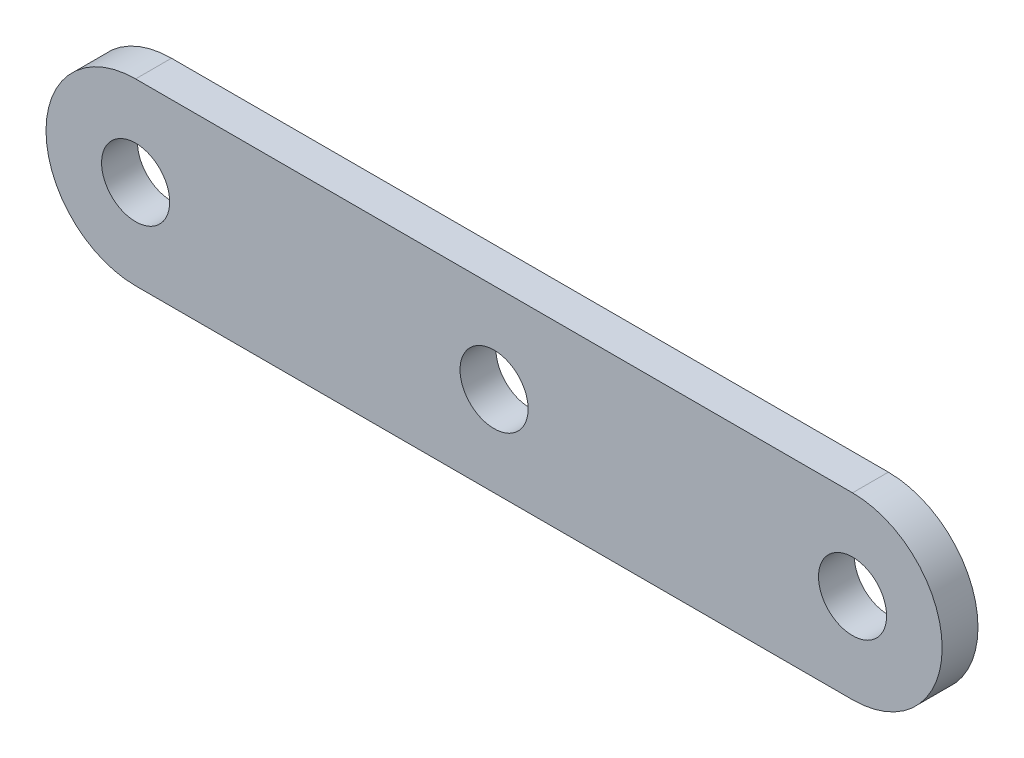
SolidWorks part; units mm, degrees
material "6061 Alloy"
ref_plane "Front Plane" through (0, 0, 0) normal (0, 0, 1) x (1, 0, 0)
ref_plane "Top Plane" through (0, 0, 0) normal (0, 1, 0) x (1, 0, 0)
ref_plane "Right Plane" through (0, 0, 0) normal (1, 0, 0) x (0, 0, -1)
sketch "Croquis1" plane through (0, 0, 0) normal (0, 0, 1) x (1, 0, 0)
  line L1 (48.26, -12.1612) -> (-2.54, -12.1612)
  line L3 (48.26, 0.5388) -> (-2.54, 0.5388)
  arc A0 (-2.54, 0.5388) -> (-2.54, -12.1612) centre (-2.54, -5.8112) ccw
  arc A1 (48.26, 0.5388) -> (48.26, -12.1612) centre (48.26, -5.8112) cw
  point P0 (0, 0)
  dimension "D2" = 6.35
  dimension "D1" = 50.8
extrude "Saliente-Extruir1" add sketch "Croquis1" along normal mid plane 2.54
sketch "Croquis2" plane through (0, 0, 1.27) normal (0, 0, 1) x (1, 0, 0)
  circle A0 centre (-2.54, -5.8112) radius 2.413
  dimension "D1" = 4.826
extrude "Cortar-Extruir1" cut sketch "Croquis2" against normal through all
pattern_linear "MatrizL1" count 3 spacing 25.4 along (1, 0, 0) of "Cortar-Extruir1"
